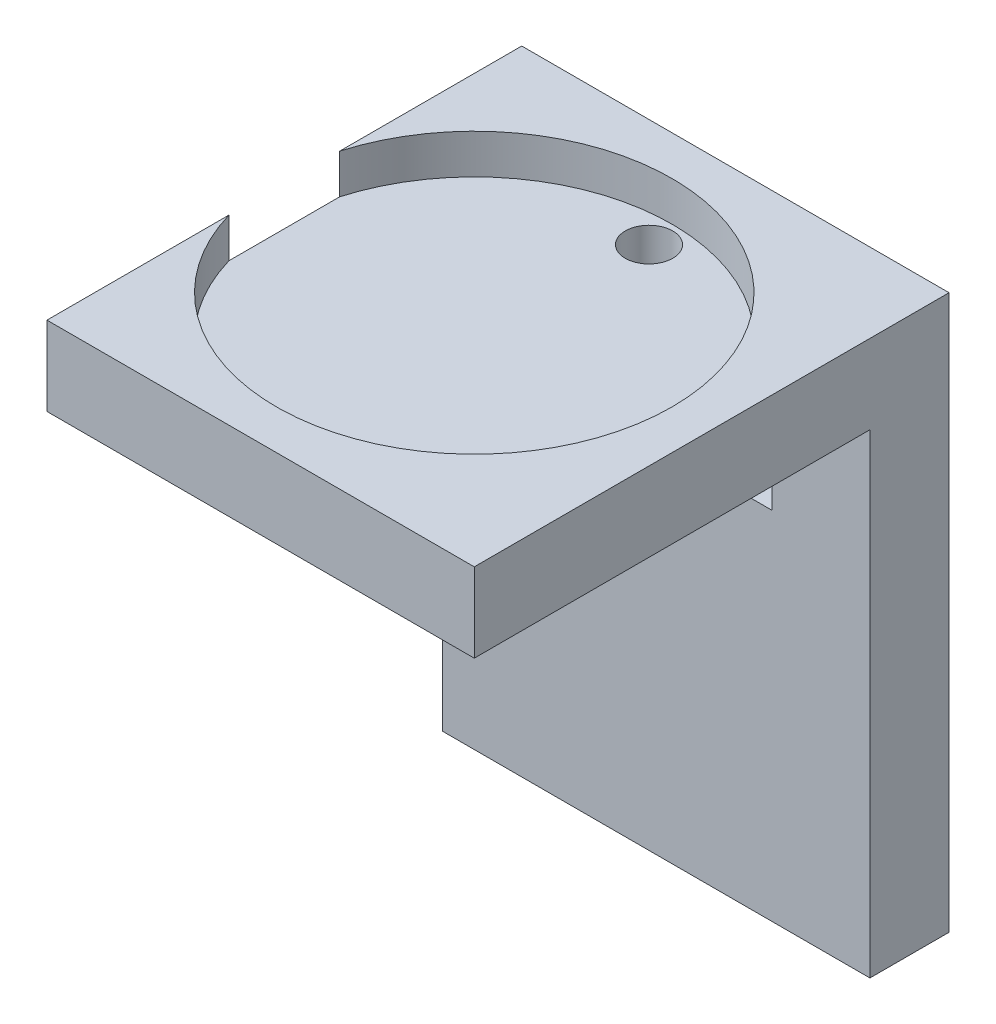
SolidWorks part; units mm, degrees
ref_plane "정면" through (0, 0, 0) normal (0, 0, 1) x (1, 0, 0)
ref_plane "윗면" through (0, 0, 0) normal (0, 1, 0) x (1, 0, 0)
ref_plane "우측면" through (0, 0, 0) normal (1, 0, 0) x (0, 0, -1)
sketch "Sketch1" plane through (0, 0, 0) normal (0, 1, 0) x (1, 0, 0)
  line L1 (0, 0) -> (670, 0)
  line L2 (0, 0) -> (0, 120)
  line L3 (0, 120) -> (670, 120)
  line L4 (670, 0) -> (670, 120)
  dimension "700" = 670
  dimension "D2" = 120
extrude "Boss-Extrude1" add sketch "Sketch1" along normal blind 530
sketch "Sketch2" plane through (0, 0, 0) normal (0, 0, 1) x (1, 0, 0)
  line L0 (0, 530) -> (0, 0) construction
  line L1 (10, 280) -> (110, 280)
  line L2 (10, 280) -> (10, 480)
  line L3 (10, 480) -> (110, 480)
  line L4 (110, 280) -> (110, 480)
  line L5 (0, 0) -> (670, 0) construction
  line L6 (120, 280) -> (120, 480)
  line L7 (120, 280) -> (220, 280)
  line L8 (220, 280) -> (220, 480)
  line L9 (120, 480) -> (220, 480)
  line L10 (230, 280) -> (230, 480)
  line L11 (230, 280) -> (330, 280)
  line L12 (330, 280) -> (330, 480)
  line L13 (230, 480) -> (330, 480)
  line L14 (340, 280) -> (340, 480)
  line L15 (340, 280) -> (440, 280)
  line L16 (440, 280) -> (440, 480)
  line L17 (340, 480) -> (440, 480)
  line L18 (450, 280) -> (450, 480)
  line L19 (450, 280) -> (550, 280)
  line L20 (550, 280) -> (550, 480)
  line L21 (450, 480) -> (550, 480)
  line L22 (560, 280) -> (560, 480)
  line L23 (560, 280) -> (660, 280)
  line L24 (660, 280) -> (660, 480)
  line L25 (560, 480) -> (660, 480)
  line L27 (10, 10) -> (660, 10)
  line L28 (10, 10) -> (10, 260)
  line L29 (10, 260) -> (660, 260)
  line L30 (660, 10) -> (660, 260)
  line L31 (0, 530) -> (670, 530) construction
  point P6 (10, 380)
  dimension "D1" = 100
  dimension "D2" = 200
  dimension "D3" = 10
  dimension "D4" = 50
  dimension "D6" = 10
  dimension "D7" = 20
  dimension "D5" = 6
extrude "Cut-Extrude1" cut sketch "Sketch2" against normal blind 100
sketch "Sketch3" plane through (0, 530, 0) normal (0, 1, 0) x (1, 0, 0)
  line L1 (670, 120) -> (0, 120) construction
  line L2 (0, 120) -> (0, 0) construction
  circle A0 centre (60, 60) radius 50
  circle A1 centre (170, 60) radius 50
  circle A2 centre (280, 60) radius 50
  circle A3 centre (390, 60) radius 50
  circle A4 centre (500, 60) radius 50
  circle A5 centre (610, 60) radius 50
  dimension "D1" = 100
  dimension "D2" = 10
  dimension "D3" = 10
  dimension "D4" = 6
extrude "Cut-Extrude2" cut sketch "Sketch3" against normal blind 260
hole_wizard "Ø12.0 (12) Diameter Hole2" positions "3DSketch1" profile "Sketch7" hole size "Ø12.0" standard "Ansi Metric"
sketch3d "3DSketch1"
  point P0 (59.7046, 270, -102.4117)
  point P2 (171.5567, 270, -102.6076)
  point P4 (280.8723, 270, -102.3969)
  point P6 (391.0687, 270, -102.7535)
  point P8 (500.7133, 270, -101.754)
  point P10 (609.5165, 270, -101.1227)
sketch "Sketch7" plane through (59.7046, 270, -102.4117) normal (1, 0, 0) x (0, 0, 1)
  line L0 (0, 0) -> (0, 33.6052)
  line L1 (0, 33.6052) -> (6, 30)
  line L2 (6, 30) -> (6, 0)
  line L5 (6, 0) -> (0, 0)
  line L10 (0, 33.6052) -> (-6, 30) construction
  line L11 (0, -6.35) -> (0, 107.95) construction
  dimension "구멍 지름" = 12
  dimension "구멍 깊이" = 30
  dimension "드릴 각도" = 118
sketch "Sketch8" plane through (0, 0, 0) normal (0, 0, 1) x (1, 0, 0)
  line L0 (660, 280) -> (660, 480) construction
  line L1 (10, 280) -> (660, 280)
  line L2 (10, 280) -> (10, 330)
  line L3 (10, 330) -> (660, 330)
  line L4 (660, 280) -> (660, 330)
  dimension "D1" = 50
extrude "Boss-Extrude2" add sketch "Sketch8" against normal blind 5
sketch "Sketch9" plane through (670, 0, 0) normal (1, 0, 0) x (0, 0, -1)
  line L0 (0, 530) -> (0, 0) construction
  line L1 (10, 10) -> (20, 10)
  line L2 (10, 10) -> (10, 260)
  line L3 (10, 260) -> (20, 260)
  line L4 (20, 10) -> (20, 260)
  line L5 (0, 0) -> (120, 0) construction
  dimension "D1" = 10
  dimension "D2" = 10
  dimension "D3" = 10
  dimension "D4" = 250
extrude "Cut-Extrude3" cut sketch "Sketch9" against normal blind 717
sketch "Sketch10" plane through (0, 10, 0) normal (0, 1, 0) x (1, 0, 0)
  line L0 (670, 120) -> (0, 120) construction
  line L1 (365, 61.9436) -> (350, 87.9243)
  line L2 (350, 87.9243) -> (320, 87.9243)
  line L3 (320, 87.9243) -> (305, 61.9436)
  line L4 (305, 61.9436) -> (320, 35.9628)
  line L5 (320, 35.9628) -> (350, 35.9628)
  line L6 (350, 35.9628) -> (365, 61.9436)
  line L7 (0, 120) -> (0, 0) construction
  circle A0 centre (335, 61.9436) radius 25.9808 construction
  dimension "D1" = 60
  dimension "D2" = 305
extrude "Cut-Extrude4" cut sketch "Sketch10" against normal blind 5
sketch "Sketch11" plane through (0, 0, -100) normal (0, 0, 1) x (1, 0, 0)
  line L0 (10, 10) -> (660, 10) construction
  line L1 (250, 10) -> (260, 10)
  line L2 (250, 10) -> (250, 110)
  line L3 (250, 110) -> (260, 110)
  line L4 (260, 10) -> (260, 110)
  line L5 (660, 10) -> (660, 260) construction
  line L6 (410, 10) -> (420, 10)
  line L7 (410, 10) -> (410, 110)
  line L8 (410, 110) -> (420, 110)
  line L9 (420, 10) -> (420, 110)
  line L10 (25, 198.4569) -> (325, 145.5588)
  line L11 (325, 145.5588) -> (325, 122.0178)
  line L12 (325, 122.0178) -> (345, 122.0178)
  line L13 (345, 122.0178) -> (345, 145.5588)
  line L14 (345, 145.5588) -> (645, 198.4569)
  line L15 (645, 198.4569) -> (25, 198.4569)
  point P18 (345, 133.7883)
  dimension "D1" = 10
  dimension "D2" = 10
  dimension "D3" = 100
  dimension "D4" = 100
  dimension "D5" = 150
  dimension "D6" = 240
  dimension "D7" = 20
  dimension "D8" = 65
  dimension "D9" = 100
  dimension "D10" = 620
  dimension "D11" = 100
extrude "Boss-Extrude3" add sketch "Sketch11" along normal blind 78 separate body
sketch "Sketch12" plane through (0, 0, -100) normal (0, 0, 1) x (1, 0, 0)
  line L0 (660, 260) -> (10, 260) construction
  line L1 (75.1986, 260) -> (95.1986, 260)
  line L2 (75.1986, 260) -> (75.1986, 230)
  line L3 (75.1986, 230) -> (95.1986, 230)
  line L4 (95.1986, 260) -> (95.1986, 230)
  line L5 (65.1986, 260) -> (65.1986, 240) construction
  line L6 (185.1986, 260) -> (185.1986, 230)
  line L7 (185.1986, 260) -> (205.1986, 260)
  line L8 (205.1986, 260) -> (205.1986, 230)
  line L9 (185.1986, 230) -> (205.1986, 230)
  line L10 (295.1986, 260) -> (295.1986, 230)
  line L11 (295.1986, 260) -> (315.1986, 260)
  line L12 (315.1986, 260) -> (315.1986, 230)
  line L13 (295.1986, 230) -> (315.1986, 230)
  line L14 (405.1986, 260) -> (405.1986, 230)
  line L15 (405.1986, 260) -> (425.1986, 260)
  line L16 (425.1986, 260) -> (425.1986, 230)
  line L17 (405.1986, 230) -> (425.1986, 230)
  line L18 (515.1986, 260) -> (515.1986, 230)
  line L19 (515.1986, 260) -> (535.1986, 260)
  line L20 (535.1986, 260) -> (535.1986, 230)
  line L21 (515.1986, 230) -> (535.1986, 230)
  line L22 (625.1986, 260) -> (625.1986, 230)
  line L23 (625.1986, 260) -> (645.1986, 260)
  line L24 (645.1986, 260) -> (645.1986, 230)
  line L25 (625.1986, 230) -> (645.1986, 230)
  dimension "D1" = 20
  dimension "D2" = 30
  dimension "D3" = 10
  dimension "D4" = 6
extrude "Cut-Extrude5" cut sketch "Sketch12" against normal blind 80
sketch "Sketch15" plane through (345, 0, 0) normal (1, 0, 0) x (0, 0, -1)
  line L0 (20, 10) -> (20, 260) construction
  line L1 (20, 121.4638) -> (50, 121.4638)
  line L2 (20, 121.4638) -> (20, 145)
  line L3 (20, 145) -> (50, 145)
  line L4 (50, 121.4638) -> (50, 145)
  line L5 (120, 530) -> (120, 0) construction
  line L6 (100, 116.0134) -> (70, 116.0134)
  line L7 (100, 116.0134) -> (100, 145)
  line L8 (100, 145) -> (70, 145)
  line L9 (70, 116.0134) -> (70, 145)
  line L10 (20, 260) -> (10, 260) construction
  dimension "D1" = 20
  dimension "D2" = 20
  dimension "D3" = 115
  dimension "D4" = 30
extrude "Cut-Extrude7" cut sketch "Sketch15" against normal blind 35
shell "Shell1" thickness 3
sketch "Sketch16" plane through (0, 122.0178, 0) normal (0, -1, 0) x (1, 0, 0)
  line L0 (345, -50) -> (325, -50) construction
  line L1 (328, -53) -> (342, -53)
  line L2 (328, -53) -> (328, -67)
  line L3 (328, -67) -> (342, -67)
  line L4 (342, -53) -> (342, -67)
  line L5 (325, -50) -> (325, -70) construction
  line L6 (345, -50) -> (345, -70) construction
  line L7 (325, -70) -> (345, -70) construction
  dimension "D1" = 3
  dimension "D2" = 3
  dimension "D3" = 3
  dimension "D4" = 3
extrude "Cut-Extrude8" cut sketch "Sketch16" against normal blind 35
sketch "Sketch17" plane through (0, 0, 0) normal (0, 0, 1) x (1, 0, 0)
  text T0 "<b>DIFF_USER</b>" font "Britannic Bold" height in points 72
extrude "Boss-Extrude4" add sketch "Sketch17" along normal blind 5
sketch "Sketch18" plane through (0, 0, 0) normal (0, 0, 1) x (1, 0, 0)
  line L0 (0, 530) -> (670, 530) construction
  line L1 (0, 530) -> (670, 530)
  line L2 (0, 530) -> (0, 280)
  line L3 (0, 280) -> (670, 280)
  line L4 (670, 530) -> (670, 280)
  line L5 (670, 530) -> (670, 0) construction
  line L6 (0, 0) -> (670, 0) construction
  dimension "D1" = 280
extrude "Cut-Extrude10" cut sketch "Sketch18" against normal through all both and the other way through all
delete or keep bodies "Body-Delete/Keep 1" type delete bodies bodies 112
delete or keep bodies "Body-Delete/Keep 2" type delete bodies bodies 109
delete or keep bodies "Body-Delete/Keep 3" type delete bodies bodies 115
sketch "Sketch19" plane through (0, 0, -100) normal (0, 0, 1) x (1, 0, 0)
  line L0 (670, 280) -> (0, 280) construction
  line L6 (670, 0) -> (230, 0)
  line L7 (670, 0) -> (670, 280)
  line L8 (670, 280) -> (230, 280)
  line L9 (230, 0) -> (230, 280)
extrude "Cut-Extrude12" cut sketch "Sketch19" against normal through all both and the other way through all
sketch "Sketch20" plane through (0, 0, -120) normal (0, 0, -1) x (-1, 0, 0)
  line L0 (-230, 0) -> (0, 0) construction
  line L1 (-122, 0) -> (88.9189, 0)
  line L2 (-122, 0) -> (-122, 296.401)
  line L3 (-122, 296.401) -> (88.9189, 296.401)
  line L4 (88.9189, 0) -> (88.9189, 296.401)
  line L5 (-230, 280) -> (-230, 0) construction
  dimension "D1" = 108
extrude "Cut-Extrude14" cut sketch "Sketch20" against normal blind 156
sketch "Sketch21" plane through (0, 0, -100) normal (0, 0, 1) x (1, 0, 0)
  line L0 (230, 10) -> (230, 260) construction
  line L1 (122, 0) -> (230, 0)
  line L2 (122, 0) -> (122, 140)
  line L3 (122, 140) -> (230, 140)
  line L4 (230, 0) -> (230, 140)
  dimension "D1" = 140
extrude "Cut-Extrude15" cut sketch "Sketch21" against normal through all both and the other way through all
